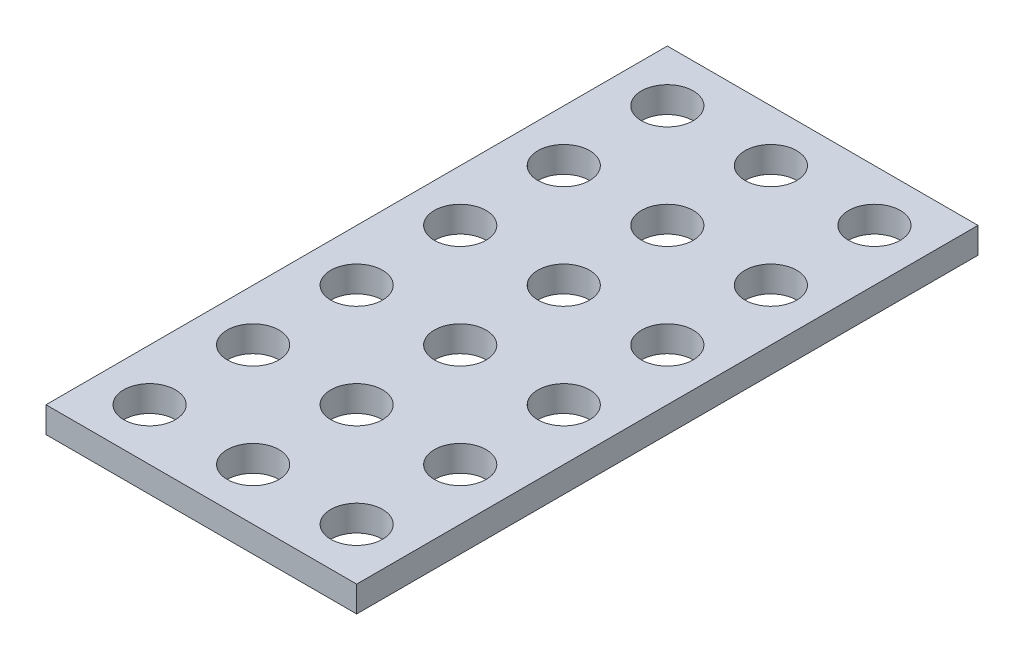
SolidWorks part; units mm, degrees
ref_plane "前视基准面" through (0, 0, 0) normal (0, 0, 1) x (1, 0, 0)
ref_plane "上视基准面" through (0, 0, 0) normal (0, 1, 0) x (1, 0, 0)
ref_plane "右视基准面" through (0, 0, 0) normal (1, 0, 0) x (0, 0, -1)
other "Configuration Table"
sketch "Sketch1" plane through (0, 0, 0) normal (0, 1, 0) x (1, 0, 0)
  line L1 (-12, 24) -> (12, 24)
  line L2 (-12, 24) -> (-12, -24)
  line L3 (-12, -24) -> (12, -24)
  line L4 (12, 24) -> (12, -24)
  line L5 (-12, 24) -> (12, -24) construction
  line L6 (-12, -24) -> (12, 24) construction
  point P0 (0, 0)
  dimension "D1" = 24
  dimension "D2" = 48
extrude "Boss-Extrude1" add sketch "Sketch1" along normal blind 2
sketch "Sketch2" plane through (0, 2, 0) normal (0, 1, 0) x (1, 0, 0)
  line L0 (-12, 24) -> (-12, -24) construction
  line L1 (12, 24) -> (-12, 24) construction
  circle A0 centre (-8, 20) radius 2
  dimension "D1" = 4
  dimension "D2" = 4
  dimension "D3" = 4
extrude "Cut-Extrude1" cut sketch "Sketch2" against normal blind 2
pattern_linear "LPattern1" count 3 spacing 8 along (1, 0, 0) count 6 spacing 8 along (0, 0, 1) of "Cut-Extrude1"
